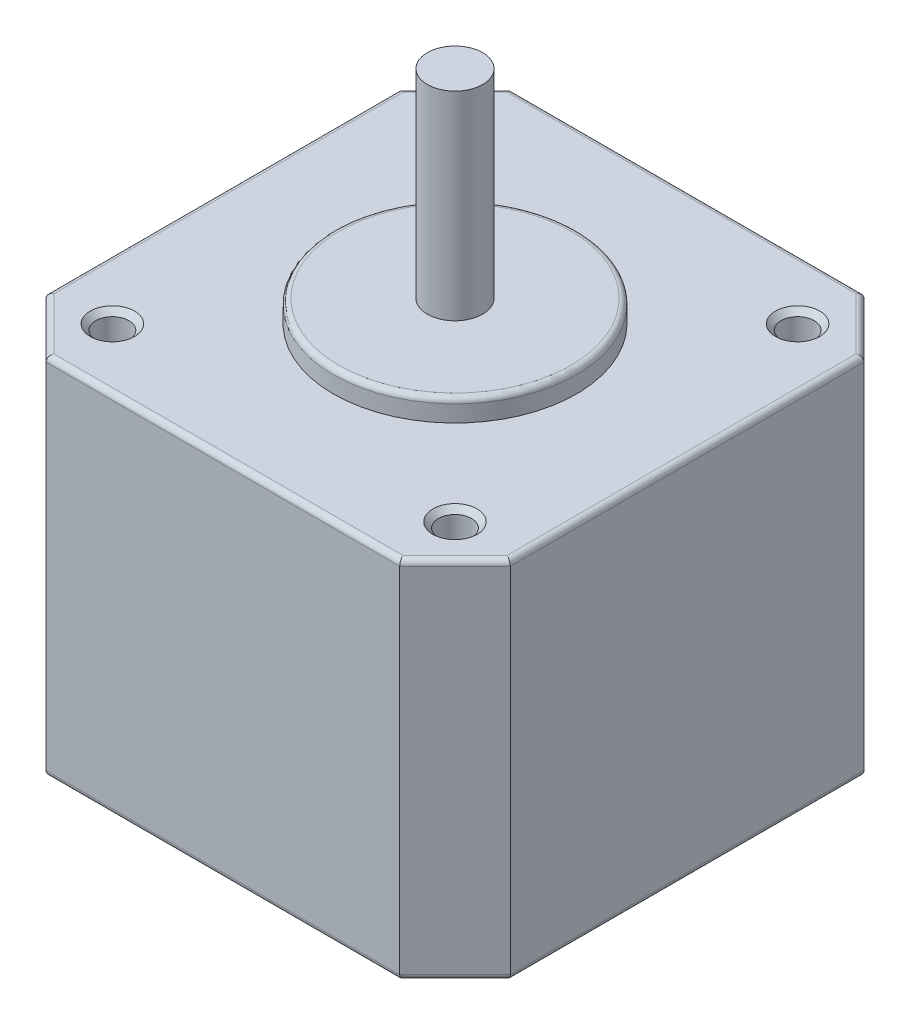
SolidWorks part; units mm, degrees
ref_plane "Front Plane" through (0, 0, 0) normal (0, 0, 1) x (1, 0, 0)
ref_plane "Top Plane" through (0, 0, 0) normal (0, 1, 0) x (1, 0, 0)
ref_plane "Right Plane" through (0, 0, 0) normal (1, 0, 0) x (0, 0, -1)
sketch "Sketch1" plane through (0, 0, 0) normal (0, 1, 0) x (1, 0, 0)
  line L0 (-21, -21) -> (21, 21) construction
  line L1 (-21, 21) -> (21, 21)
  line L2 (-21, 21) -> (-21, -21)
  line L3 (-21, -21) -> (21, -21)
  line L4 (21, 21) -> (21, -21)
  line L5 (21, -21) -> (-21, 21) construction
  dimension "D1" = 42
  dimension "D2" = 42
extrude "Boss-Extrude1" add sketch "Sketch1" along normal blind 33
sketch "Sketch2" plane through (0, 33, 0) normal (0, 1, 0) x (1, 0, 0)
  circle A0 centre (0, 0) radius 11
  dimension "D1" = 22
extrude "Boss-Extrude2" add sketch "Sketch2" along normal blind 2
sketch "Sketch3" plane through (0, 35, 0) normal (0, 1, 0) x (1, 0, 0)
  circle A0 centre (0, 0) radius 2.5
  dimension "D1" = 5
extrude "Boss-Extrude3" add sketch "Sketch3" along normal blind 18
sketch "Sketch4" plane through (0, 33, 0) normal (0, 1, 0) x (1, 0, 0)
  line L0 (15.5, 15.5) -> (-15.5, -15.5) construction
  line L1 (-15.5, 15.5) -> (15.5, 15.5)
  line L2 (-15.5, 15.5) -> (-15.5, -15.5)
  line L3 (-15.5, -15.5) -> (15.5, -15.5)
  line L4 (15.5, 15.5) -> (15.5, -15.5)
  line L5 (-15.5, 15.5) -> (15.5, -15.5) construction
  line L6 (21, 21) -> (-21, 21) construction
  line L7 (21, -21) -> (21, 21) construction
  circle A0 centre (-15.5, 15.5) radius 1.5
  circle A1 centre (15.5, 15.5) radius 1.5
  circle A2 centre (15.5, -15.5) radius 1.5
  circle A3 centre (-15.5, -15.5) radius 1.5
  dimension "D1" = 3
  dimension "D2" = 3
  dimension "D3" = 3
  dimension "D4" = 3
  dimension "D5" = 31
  dimension "D6" = 31
  dimension "D7" = 5.5
  dimension "D8" = 5.5
extrude "Cut-Extrude1" cut sketch "Sketch4" against normal blind 5 contours A3 | A2 | A1 | A0
chamfer "Chamfer1" distance 5 angle 45 4 edges at (-21, 16.5, 21) (-21, 16.5, -21) (21, 16.5, -21) (21, 16.5, 21)
chamfer "Chamfer2" distance 0.5 angle 45 4 edges at (15.5, 33, 17) (-15.5, 33, 17) (-15.5, 33, -14) (15.5, 33, -14)
fillet "Fillet1" radius 0.5 16 edges at (18.5, 0, 18.5) (21, 0, 0) (18.5, 0, -18.5) (0, 0, -21) (-18.5, 0, -18.5) (-21, 0, 0) (-18.5, 0, 18.5) (0, 0, 21) (-21, 33, 0) (-18.5, 33, -18.5) (18.5, 33, -18.5) (0, 33, -21) (21, 33, 0) (18.5, 33, 18.5) (0, 33, 21) (-18.5, 33, 18.5)
fillet "Fillet2" radius 0.5 1 edges at (0, 35, 11)
